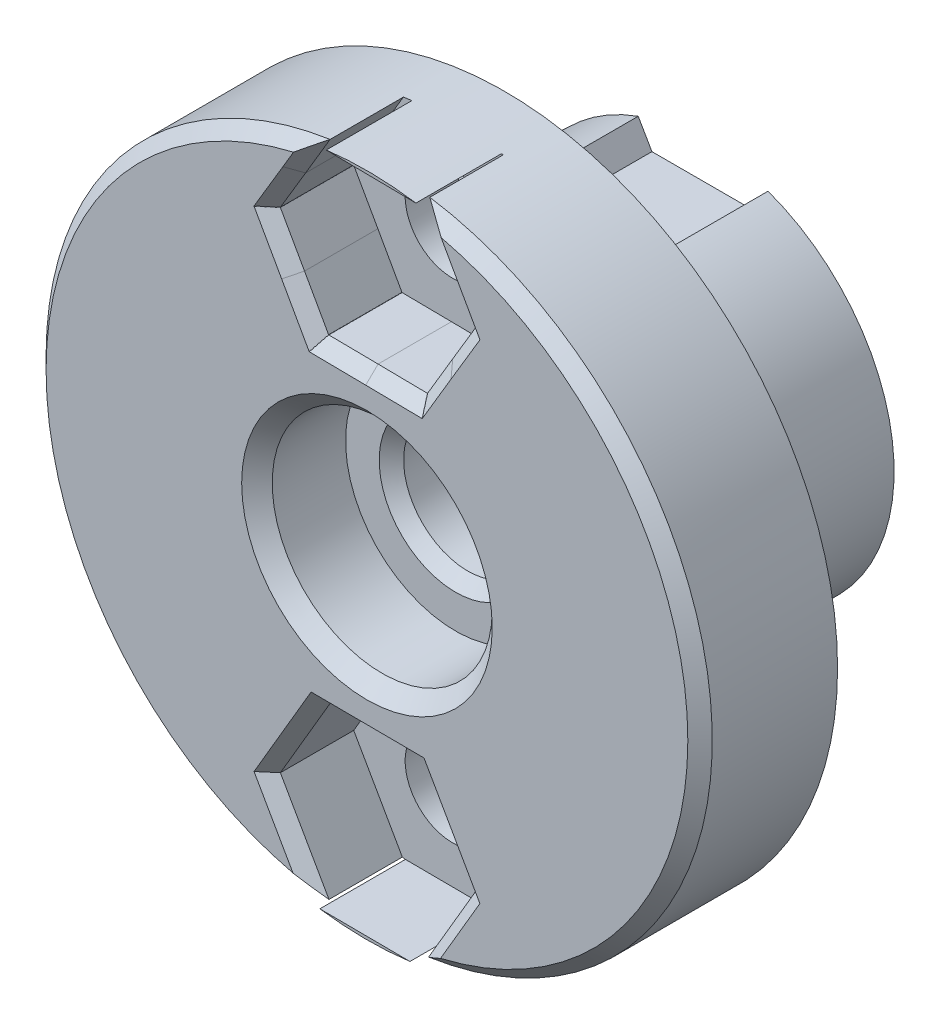
SolidWorks part; units mm, degrees
ref_plane "Front Plane" through (0, 0, 0) normal (0, 0, 1) x (1, 0, 0)
ref_plane "Top Plane" through (0, 0, 0) normal (0, 1, 0) x (1, 0, 0)
ref_plane "Right Plane" through (0, 0, 0) normal (1, 0, 0) x (0, 0, -1)
sketch "Sketch2" plane through (0, 0, 0) normal (0, 0, 1) x (1, 0, 0)
  circle A0 centre (0, 0) radius 10.9
  circle A1 centre (0, 8) radius 1.55
  circle A2 centre (0, -8) radius 1.55
  circle A3 centre (0, 0) radius 8 construction
  dimension "D1" = 3.1
  dimension "D2" = 3.1
extrude "Boss-Extrude1" add sketch "Sketch2" along normal blind 4.5
sketch "Sketch3" plane through (0, 0, 0) normal (0, 0, -1) x (-1, 0, 0)
  line L0 (-1.05, 1.05) -> (1.4849, -1.4849) construction
  circle A0 centre (0, 0) radius 6.25
  circle A2 centre (0, 0) radius 2.1
  point P7 (0, 0)
  dimension "D1" = 4.2
  dimension "D2" = 12.5
extrude "Boss-Extrude2" add sketch "Sketch3" along normal blind 6.5
sketch "Sketch6" plane through (0, 0, 0) normal (0, 0, -1) x (-1, 0, 0)
  circle A1 centre (0, 0) radius 2.1
  circle A2 centre (0, 0) radius 2.1
  dimension "D1" = 0
extrude "Cut-Extrude2" cut sketch "Sketch6" against normal blind 9.5
sketch "Sketch7" plane through (0, 0, 4.5) normal (0, 0, 1) x (1, 0, 0)
  circle A0 centre (0, 0) radius 3.6
extrude "Cut-Extrude3" cut sketch "Sketch7" against normal blind 2.9
sketch "Sketch8" plane through (0, 0, 4.5) normal (0, 0, 1) x (1, 0, 0)
  line L1 (1.584, 5.1814) -> (3.2329, 7.9625)
  line L2 (3.2329, 7.9625) -> (1.649, 10.781)
  line L3 (1.649, 10.781) -> (-1.584, 10.8186)
  line L4 (-1.584, 10.8186) -> (-3.2329, 8.0375)
  line L5 (-3.2329, 8.0375) -> (-1.649, 5.219)
  line L6 (-1.649, 5.219) -> (1.584, 5.1814)
  line L7 (3.2331, -8.0201) -> (1.634, -5.2101)
  line L8 (1.634, -5.2101) -> (-1.5991, -5.19)
  line L9 (-1.5991, -5.19) -> (-3.2331, -7.9799)
  line L10 (-3.2331, -7.9799) -> (-1.634, -10.7899)
  line L11 (-1.634, -10.7899) -> (1.5991, -10.81)
  line L12 (1.5991, -10.81) -> (3.2331, -8.0201)
  circle A0 centre (0, 8) radius 2.8 construction
  circle A1 centre (0, -8) radius 2.8 construction
  dimension "D1" = 5.6
  dimension "D2" = 5.6
extrude "Cut-Extrude4" cut sketch "Sketch8" against normal blind 2.8
chamfer "Chamfer2" distance 0.5 angle 45 1 edges at (3.6, 0, 4.5)
sketch "Sketch9" plane through (0, 0, 0) normal (0, 0, -1) x (-1, 0, 0)
  line L0 (0, 8) -> (0, -8) construction
  line L1 (-8.7127, 0) -> (8.7127, 0) construction
  point P9 (0, 0)
  dimension "D1" = 90
sketch "Sketch10" plane through (0, 0, -6.5) normal (0, 0, -1) x (-1, 0, 0)
  line L0 (-8.7127, 0) -> (8.7127, 0) construction
ref_plane "Plane1" through (-6.25, 0, 0) normal (-1, 0, 0) x (0, 1, 0)
sketch "Sketch11" plane through (-6.25, 0, 0) normal (-1, 0, 0) x (0, 1, 0)
  circle A0 centre (0, 3.2158) radius 1.55
ref_plane "Plane2" through (-3.35, 0, 0) normal (-1, 0, 0) x (0, 1, 0)
sketch "Sketch13" plane through (-3.35, 0, 0) normal (-1, 0, 0) x (0, 1, 0)
  line L1 (3.2324, 3.145) -> (1.6775, 5.9797)
  line L2 (1.6775, 5.9797) -> (-1.5549, 6.0505)
  line L3 (-1.5549, 6.0505) -> (-3.2324, 3.2865)
  line L4 (-3.2324, 3.2865) -> (-1.6775, 0.4518)
  line L5 (-1.6775, 0.4518) -> (1.5549, 0.3811)
  line L6 (1.5549, 0.3811) -> (3.2324, 3.145)
  circle A0 centre (0, 3.2158) radius 2.8 construction
  dimension "D1" = 5.6
sketch "Sketch14" plane through (0, 0, -6.5) normal (0, 0, -1) x (-1, 0, 0)
  line L0 (1.95, 3.1) -> (1.95, -3.1)
  line L1 (1.95, 3.1) -> (4.75, 3.1)
  line L2 (1.95, -3.1) -> (4.75, -3.1)
  line L3 (4.75, 3.1) -> (4.75, -3.1)
  line L4 (1.95, 3.1) -> (4.75, -3.1) construction
  line L5 (1.95, -3.1) -> (4.75, 3.1) construction
  line L6 (3.35, -2.8) -> (3.35, 2.8) construction
  point P1 (3.35, 0)
  dimension "D1" = 2.8
  dimension "D2" = 6.2
extrude "Cut-Extrude5" cut sketch "Sketch11" against normal mid plane 11 contours A0
extrude "Cut-Extrude6" cut sketch "Sketch14" against normal blind 6.4
sketch "Sketch17" plane through (0, 0, 1.7) normal (0, 0, 1) x (1, 0, 0)
  line L1 (1.6551, 10.7774) -> (-1.5778, 10.822)
  line L2 (-1.5778, 10.822) -> (-3.2329, 8.0446)
  line L3 (-3.2329, 8.0446) -> (-1.6551, 5.2226)
  line L4 (-1.6551, 5.2226) -> (1.5778, 5.178)
  line L5 (1.5778, 5.178) -> (3.2329, 7.9554)
  line L6 (3.2329, 7.9554) -> (1.6551, 10.7774)
  circle A0 centre (0, 8) radius 2.8 construction
  dimension "D1" = 5.6
extrude "Cut-Extrude8" cut sketch "Sketch17" along normal blind 6.2
chamfer "Chamfer3" distance 0.4 angle 45 25 edges at (2.4251, -9.3998, 4.5) (2.4335, -6.6151, 4.5) (0.0174, -5.2001, 4.5) (-2.4161, -6.5849, 4.5) (-2.4376, -9.3777, 4.5) (-10.9, 0.0181, 4.5) (-2.0066, 10.1058, 4.5) (-2.8199, 8.7377, 4.5) (-3.2319, 8.0428, 4.5) (-3.2319, 8.0393, 4.5) (-2.8377, 7.3342, 4.5) (-2.0488, 5.9267, 4.5) (-1.653, 5.2225, 4.5) (-1.65, 5.2207, 4.5) (-0.8423, 5.2096, 4.5) (0.7711, 5.1891, 4.5) (1.5788, 5.1797, 4.5) (1.5819, 5.1814, 4.5) (1.9954, 5.8754, 4.5) (2.8199, 7.2623, 4.5) (3.2319, 7.9572, 4.5) (3.2319, 7.9607, 4.5) (2.8377, 8.6658, 4.5) (2.0499, 10.0712, 4.5) (10.9, -0.0204, 4.5)
chamfer "Chamfer4" distance 0.4 angle 45 1 edges at (2.1, 0, 1.6)
sketch "Sketch19" plane through (0, 0, -6.5) normal (0, 0, -1) x (-1, 0, 0)
  line L0 (-8.7127, 0) -> (8.7127, 0) construction
  line L1 (5.0779, 3.5) -> (7.5779, 3.5)
  line L2 (5.0779, 3.5) -> (5.0779, -3.5)
  line L3 (5.0779, -3.5) -> (7.5779, -3.5)
  line L4 (7.5779, 3.5) -> (7.5779, -3.5)
  dimension "D1" = 3.5
  dimension "D2" = 3.5
  dimension "D3" = 2.5
extrude "Boss-Extrude4" add sketch "Sketch19" against normal blind 10
fillet "Fillet5" radius 3 2 edges at (-5.1781, -3.5, -3.25) (-5.1781, 3.5, -3.25)
sketch "Sketch20" plane through (0, 0, -6.5) normal (0, 0, -1) x (-1, 0, 0)
  line L1 (1.6743, 10.9) -> (-1.6743, 10.9)
  line L2 (-1.6743, 10.9) -> (-3.3486, 8)
  line L3 (-3.3486, 8) -> (-1.6743, 5.1)
  line L4 (-1.6743, 5.1) -> (1.6743, 5.1)
  line L5 (1.6743, 5.1) -> (3.3486, 8)
  line L6 (3.3486, 8) -> (1.6743, 10.9)
  line L7 (1.6743, -5.1) -> (-1.6743, -5.1)
  line L8 (-1.6743, -5.1) -> (-3.3486, -8)
  line L9 (-3.3486, -8) -> (-1.6743, -10.9)
  line L10 (-1.6743, -10.9) -> (1.6743, -10.9)
  line L11 (1.6743, -10.9) -> (3.3486, -8)
  line L12 (3.3486, -8) -> (1.6743, -5.1)
  circle A0 centre (0, 8) radius 2.9 construction
  circle A1 centre (0, -8) radius 2.9 construction
  dimension "D1" = 5.8
extrude "Cut-Extrude9" cut sketch "Sketch20" against normal up to surface (6.5 mm away) up to face at (-4.3894, 0, 0)
sketch "Sketch21" plane through (-5.0779, 0, 0) normal (1, 0, 0) x (0, 0, -1)
  circle A0 centre (3.2158, 0) radius 1.55
extrude "Cut-Extrude10" cut sketch "Sketch21" against normal blind 87
